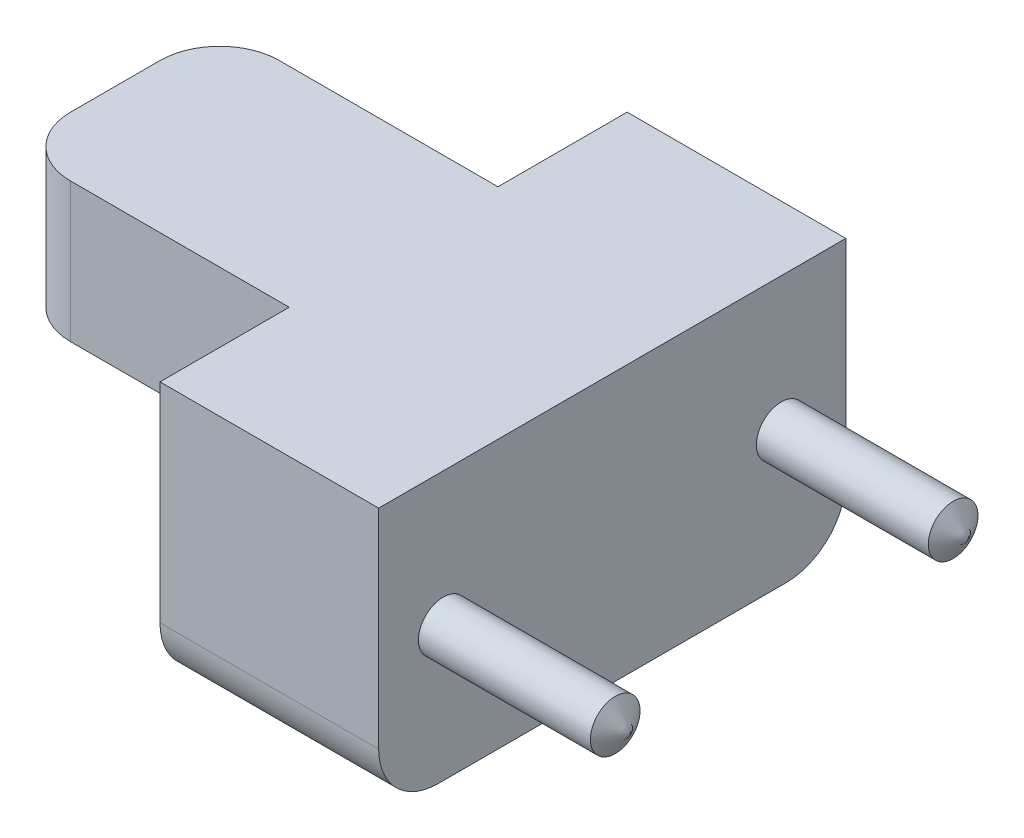
SolidWorks part; units mm, degrees
material "Abzugskörper"
ref_plane "Ebene vorne" through (0, 0, 0) normal (0, 0, 1) x (1, 0, 0)
ref_plane "Ebene oben" through (0, 0, 0) normal (0, 1, 0) x (1, 0, 0)
ref_plane "Ebene rechts" through (0, 0, 0) normal (1, 0, 0) x (0, 0, -1)
sketch "Skizze1" plane through (0, 0, 0) normal (0, 1, 0) x (1, 0, 0)
  line L1 (0, 23.501) -> (22, 23.501)
  line L2 (0, 23.501) -> (0, -23.501)
  line L3 (0, -23.501) -> (22, -23.501)
  line L4 (22, 23.501) -> (22, -23.501)
  point P4 (22, 0)
  dimension "#l1" = 22
  dimension "#b2" = 47.002
extrude "Aufsatz-Linear austragen1" add sketch "Skizze1" along normal blind 27
fillet "Verrundung1" radius 6 2 edges at (11, 0, 23.501) (11, 0, -23.501)
sketch "Skizze2" plane through (0, 0, 0) normal (-1, 0, 0) x (0, 0, 1)
  line L0 (-23.501, 27) -> (23.501, 27) construction
  line L1 (-10.5, 27) -> (10.5, 27)
  line L2 (-10.5, 27) -> (-10.5, 13)
  line L3 (-10.5, 13) -> (10.5, 13)
  line L4 (10.5, 27) -> (10.5, 13)
  point P6 (0, 13)
  dimension "#b1" = 21
  dimension "#t2" = 14
extrude "Aufsatz-Linear austragen2" add sketch "Skizze2" along normal blind 28
fillet "Verrundung2" radius 6 2 edges at (-28, 20, -10.5) (-28, 20, 10.5)
sketch "Skizze3" plane through (22, 0, 0) normal (1, 0, 0) x (0, 0, -1)
  line L0 (0, 0) -> (0, 27) construction
  line L1 (-17.501, 0) -> (17.501, 0) construction
  line L2 (-23.501, 27) -> (23.501, 27) construction
  line L3 (17, 13.5) -> (0, 13.5) construction
  line L4 (0, 13.5) -> (-17, 13.5) construction
  circle A0 centre (17, 13.5) radius 2.5
  circle A1 centre (-17, 13.5) radius 2.5
  dimension "d5" = 5
  dimension "a2" = 13.5
  dimension "a1" = 34
extrude "Aufsatz-Linear austragen3" add sketch "Skizze3" along normal blind 17.3
ref_plane "Ebene1" through (0, 13.5, 0) normal (0, 1, 0) x (-1, 0, 0)
sketch "Skizze4" plane through (0, 13.5, 0) normal (0, 1, 0) x (-1, 0, 0)
  line L0 (-39.3, 19.5) -> (-39.3, 14.5) construction
  line L1 (-39.3, 19.5) -> (-39.3, 14.5) construction
  line L2 (-39.3, 17) -> (-45.6918, 17) construction
  line L3 (-39.3, 14.5) -> (-40.8022, 17)
  line L4 (-40.8022, 17) -> (-39.3, 17)
  line L5 (-39.3, 14.5) -> (-39.3, 17)
  dimension "w1" = 59
revolve "Rotation2" add sketch "Skizze4" angle 360 about L2
sketch "Skizze5" plane through (0, 13.5, 0) normal (0, 1, 0) x (-1, 0, 0)
  line L0 (-39.3, -14.5) -> (-39.3, -19.5) construction
  line L1 (-39.3, -14.5) -> (-39.3, -19.5) construction
  line L2 (-39.3, -19.5) -> (-39.3, -17)
  line L3 (-39.3, -17) -> (-40.8022, -17)
  line L4 (-40.8022, -17) -> (-39.3, -19.5)
  line L5 (-39.3, -17) -> (-43.4801, -17) construction
  dimension "w1" = 59
revolve "Rotation3" add sketch "Skizze5" angle 360 about L5
